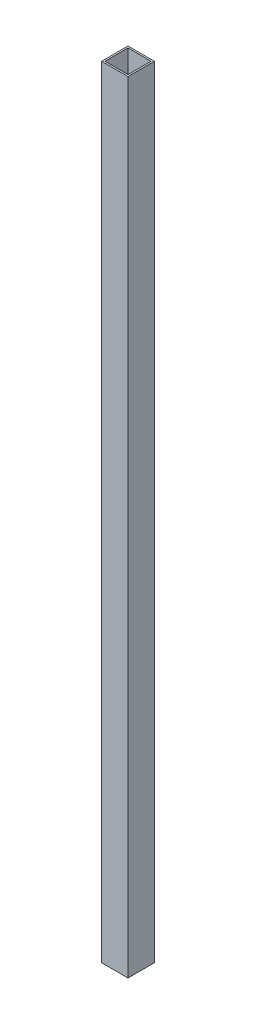
SolidWorks part; units mm, degrees
ref_plane "Front Plane" through (0, 0, 0) normal (0, 0, 1) x (1, 0, 0)
ref_plane "Top Plane" through (0, 0, 0) normal (0, 1, 0) x (1, 0, 0)
ref_plane "Right Plane" through (0, 0, 0) normal (1, 0, 0) x (0, 0, -1)
sketch "Sketch1" plane through (0, 0, 0) normal (0, 1, 0) x (1, 0, 0)
  line L0 (1.2, -1.2) -> (1.2, -17.8)
  line L1 (0, 0) -> (19, 0)
  line L2 (0, 0) -> (0, -19)
  line L3 (0, -19) -> (19, -19)
  line L4 (19, 0) -> (19, -19)
  line L5 (1.2, -17.8) -> (17.8, -17.8)
  line L6 (17.8, -1.2) -> (17.8, -17.8)
  line L7 (1.2, -1.2) -> (17.8, -1.2)
  dimension "D1" = 19
  dimension "D2" = 1.2
extrude "Boss-Extrude1" add sketch "Sketch1" along normal blind 562
